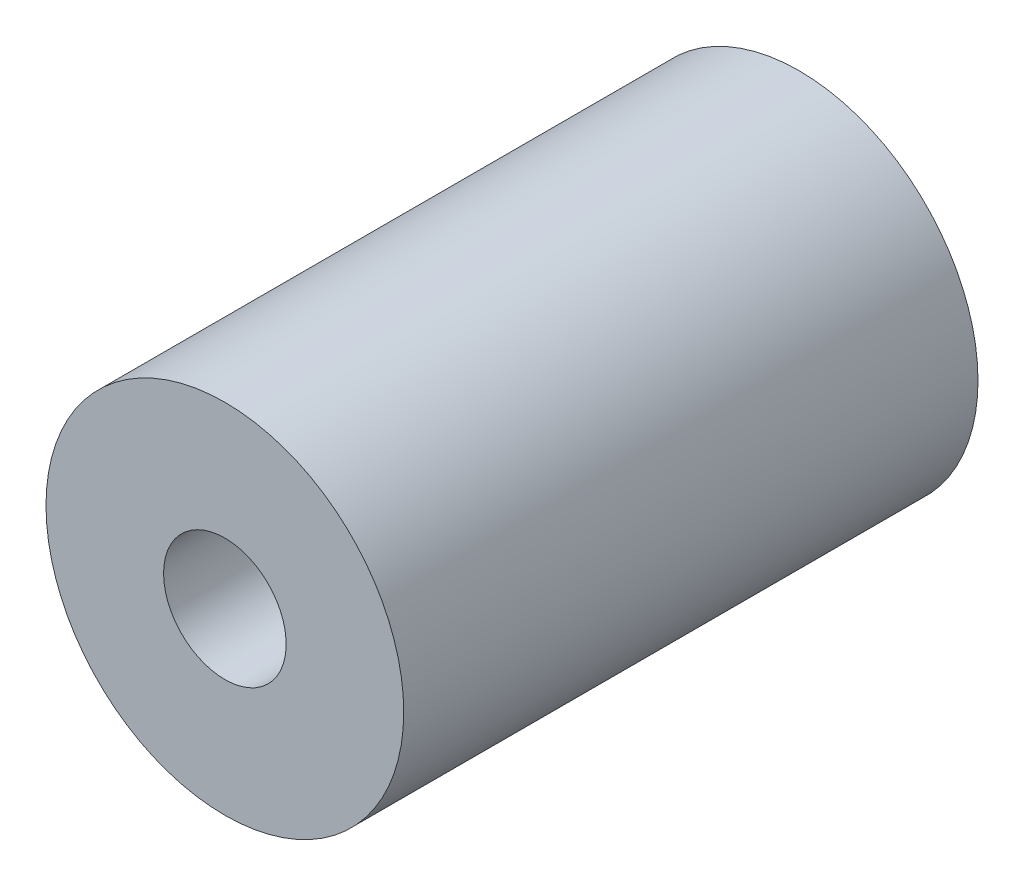
SolidWorks part; units mm, degrees
material "6061-T6 (SS)"
ref_plane "Front Plane" through (0, 0, 0) normal (0, 0, 1) x (1, 0, 0)
ref_plane "Top Plane" through (0, 0, 0) normal (0, 1, 0) x (1, 0, 0)
ref_plane "Right Plane" through (0, 0, 0) normal (1, 0, 0) x (0, 0, -1)
sketch "Sketch1" plane through (0, 0, 0) normal (1, 0, 0) x (0, 0, -1)
  line L0 (21.7309, 0) -> (-28.9169, 0) construction
  line L1 (-15.2908, 9.525) -> (-15.2908, 3.2639)
  line L2 (-15.2908, 9.525) -> (15.2908, 9.525)
  line L3 (-15.2908, 3.2639) -> (15.2908, 3.2639)
  line L4 (15.2908, 9.525) -> (15.2908, 3.2639)
  point P3 (0, 3.2639)
  dimension "D1" = 19.05
  dimension "D2" = 6.5278
  dimension "D3" = 30.5816
revolve "Revolve1" add sketch "Sketch1" angle 360 about L0
